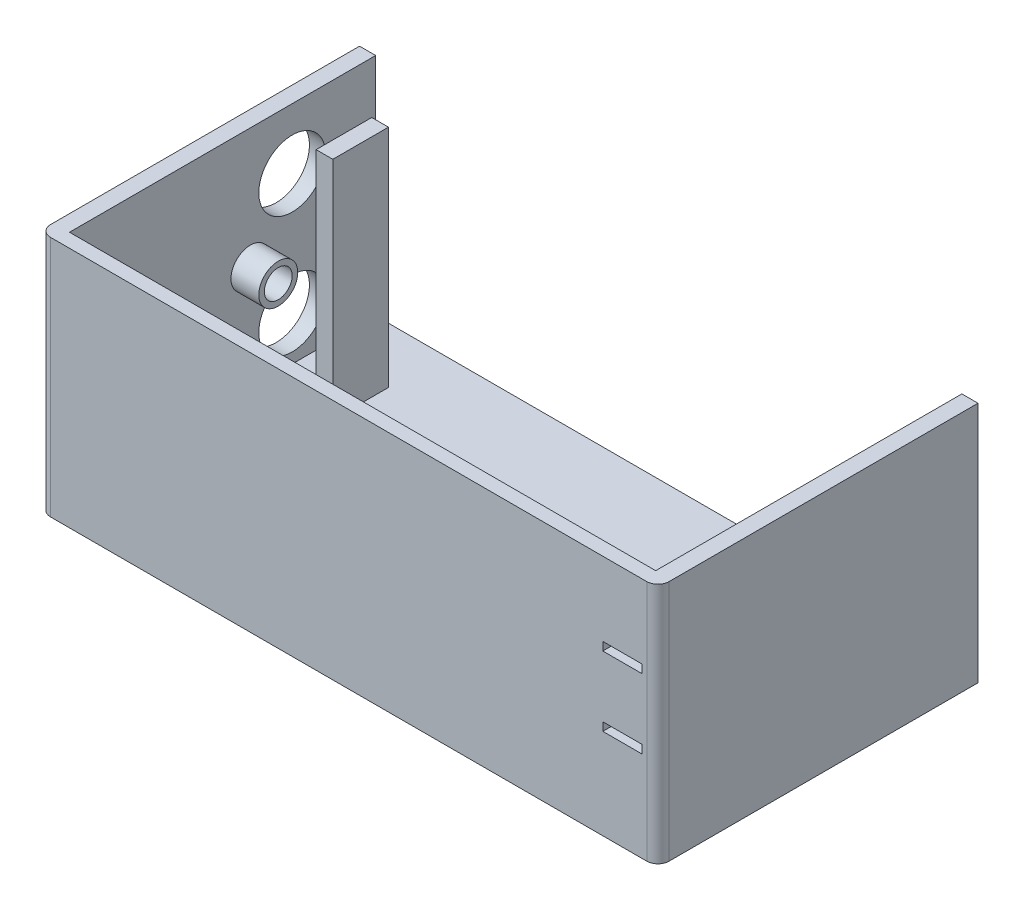
SolidWorks part; units mm, degrees
ref_plane "Front Plane" through (0, 0, 0) normal (0, 0, 1) x (1, 0, 0)
ref_plane "Top Plane" through (0, 0, 0) normal (0, 1, 0) x (1, 0, 0)
ref_plane "Right Plane" through (0, 0, 0) normal (1, 0, 0) x (0, 0, -1)
sketch "Sketch1" plane through (0, 0, 0) normal (0, 1, 0) x (1, 0, 0)
  line L1 (55.55, -30) -> (-55.55, -30)
  line L2 (55.55, -30) -> (55.55, 30)
  line L3 (55.55, 30) -> (-55.55, 30)
  line L4 (-55.55, -30) -> (-55.55, 30)
  line L5 (55.55, -30) -> (-55.55, 30) construction
  line L6 (55.55, 30) -> (-55.55, -30) construction
  point P0 (0, 0)
  dimension "D1" = 111.1
  dimension "D2" = 60
extrude "Boss-Extrude1" add sketch "Sketch1" along normal blind 3
sketch "Sketch2" plane through (0, 3, 0) normal (0, 1, 0) x (1, 0, 0)
  line L1 (52.65, -27.5) -> (-52.65, -27.5)
  line L2 (52.65, -27.5) -> (52.65, 27.5)
  line L3 (52.65, 27.5) -> (-52.65, 27.5)
  line L4 (-52.65, -27.5) -> (-52.65, 27.5)
  line L5 (52.65, -27.5) -> (-52.65, 27.5) construction
  line L6 (52.65, 27.5) -> (-52.65, -27.5) construction
  line L7 (55.55, 30) -> (-55.55, 30)
  line L8 (55.55, 30) -> (55.55, -30)
  line L9 (55.55, -30) -> (-55.55, -30)
  line L10 (-55.55, 30) -> (-55.55, -30)
  line L11 (55.55, 30) -> (-55.55, -30) construction
  line L12 (55.55, -30) -> (-55.55, 30) construction
  point P0 (0, 0)
  point P6 (0, 0)
  dimension "D1" = 105.3
  dimension "D2" = 55
extrude "Boss-Extrude2" add sketch "Sketch2" along normal blind 40.5
sketch "Sketch5" plane through (0, 0, -30) normal (0, 0, -1) x (-1, 0, 0)
  line L0 (0, 43.5) -> (0, 0) construction
  line L1 (-55.55, 43.5) -> (55.55, 43.5) construction
  line L2 (-55.55, 43.5) -> (0, 43.5) construction
  line L3 (-27.775, 43.5) -> (-27.775, 0) construction
  line L4 (-55.55, 0) -> (55.55, 0) construction
  circle A0 centre (-27.775, 21.75) radius 21
  circle A1 centre (27.775, 21.75) radius 21
  dimension "D1" = 42
extrude "Boss-Extrude4" add sketch "Sketch5" along normal blind 15
sketch "Sketch6" plane through (0, 0, -45) normal (0, 0, -1) x (-1, 0, 0)
  line L0 (-27.775, 42.75) -> (-27.775, 0.75) construction
  line L1 (27.775, 42.75) -> (27.775, 0.75) construction
  line L3 (-20.025, 3.25) -> (-35.525, 3.25)
  line L4 (-20.025, 3.25) -> (-20.025, 40.25)
  line L5 (-20.025, 40.25) -> (-35.525, 40.25)
  line L6 (-35.525, 3.25) -> (-35.525, 40.25)
  line L7 (-20.025, 3.25) -> (-35.525, 40.25) construction
  line L8 (-20.025, 40.25) -> (-35.525, 3.25) construction
  line L9 (35.525, 3.25) -> (20.025, 3.25)
  line L10 (35.525, 3.25) -> (35.525, 40.25)
  line L11 (35.525, 40.25) -> (20.025, 40.25)
  line L12 (20.025, 3.25) -> (20.025, 40.25)
  line L13 (35.525, 3.25) -> (20.025, 40.25) construction
  line L14 (35.525, 40.25) -> (20.025, 3.25) construction
  circle A0 centre (-27.775, 21.75) radius 21 construction
  circle A1 centre (-27.775, 21.75) radius 21 construction
  circle A2 centre (27.775, 21.75) radius 21 construction
  circle A3 centre (27.775, 21.75) radius 21 construction
  point P14 (-27.775, 21.75)
  point P19 (27.775, 21.75)
  dimension "D1" = 15.5
  dimension "D2" = 37
extrude "Cut-Extrude1" cut sketch "Sketch6" against normal blind 21
sketch "Sketch8" plane through (0, 0, -45) normal (0, 0, -1) x (-1, 0, 0)
  line L0 (-27.775, 42.75) -> (-27.775, 0.75) construction
  line L2 (-21.625, 4.6) -> (-33.925, 4.6)
  line L3 (-21.625, 4.6) -> (-21.625, 38.9)
  line L4 (-21.625, 38.9) -> (-33.925, 38.9)
  line L5 (-33.925, 4.6) -> (-33.925, 38.9)
  line L6 (-21.625, 4.6) -> (-33.925, 38.9) construction
  line L7 (-21.625, 38.9) -> (-33.925, 4.6) construction
  circle A0 centre (-27.775, 21.75) radius 21 construction
  circle A1 centre (-27.775, 21.75) radius 21 construction
  circle A2 centre (-27.775, 21.75) radius 21
  dimension "D1" = 12.3
  dimension "D2" = 34.3
extrude "Boss-Extrude5" add sketch "Sketch8" against normal blind 1
sketch "Sketch9" plane through (0, 0, -45) normal (0, 0, -1) x (-1, 0, 0)
  line L0 (27.775, 42.75) -> (27.775, 0.75) construction
  line L2 (33.925, 4.6) -> (21.625, 4.6)
  line L3 (33.925, 4.6) -> (33.925, 38.9)
  line L4 (33.925, 38.9) -> (21.625, 38.9)
  line L5 (21.625, 4.6) -> (21.625, 38.9)
  line L6 (33.925, 4.6) -> (21.625, 38.9) construction
  line L7 (33.925, 38.9) -> (21.625, 4.6) construction
  circle A0 centre (27.775, 21.75) radius 21 construction
  circle A1 centre (27.775, 21.75) radius 21 construction
  circle A2 centre (27.775, 21.75) radius 21
  point P7 (27.775, 21.75)
  dimension "D1" = 12.3
  dimension "D2" = 34.3
extrude "Boss-Extrude6" add sketch "Sketch9" against normal blind 1
sketch "Sketch10" plane through (0, 0, -27.5) normal (0, 0, 1) x (1, 0, 0)
  line L0 (0, 43.5) -> (0, 0) construction
  line L1 (-55.55, 43.5) -> (55.55, 43.5) construction
  line L3 (63.1223, -12.5986) -> (-63.1223, -12.5986)
  line L4 (63.1223, -12.5986) -> (63.1223, 56.0986)
  line L5 (63.1223, 56.0986) -> (-63.1223, 56.0986)
  line L6 (-63.1223, -12.5986) -> (-63.1223, 56.0986)
  line L7 (63.1223, -12.5986) -> (-63.1223, 56.0986) construction
  line L8 (63.1223, 56.0986) -> (-63.1223, -12.5986) construction
  point P5 (0, 21.75)
extrude "Cut-Extrude3" cut sketch "Sketch10" against normal blind 53
sketch "Sketch12" plane through (0, 0, -27.5) normal (0, 0, -1) x (-1, 0, 0)
  line L0 (52.65, 8.7) -> (51.65, 8.7)
  line L1 (52.65, 43.5) -> (52.65, 3) construction
  line L2 (51.65, 8.7) -> (51.65, 7.2)
  line L3 (51.65, 7.2) -> (52.65, 7.2)
  line L4 (0, 43.5) -> (0, 0) construction
  line L5 (52.65, 43.5) -> (-52.65, 43.5) construction
  line L6 (0, 21.75) -> (55.55, 21.75) construction
  line L7 (55.55, 43.5) -> (55.55, 0) construction
  line L8 (52.65, 25.35) -> (51.65, 25.35)
  line L9 (51.65, 25.35) -> (51.65, 23.85)
  line L10 (51.65, 23.85) -> (52.65, 23.85)
  line L11 (52.65, 23.85) -> (52.65, 25.35)
  line L12 (52.65, 19.65) -> (52.65, 18.15)
  line L13 (51.65, 19.65) -> (52.65, 19.65)
  line L14 (51.65, 18.15) -> (51.65, 19.65)
  line L15 (52.65, 18.15) -> (51.65, 18.15)
  line L16 (52.65, 3) -> (-52.65, 3) construction
  line L18 (-51.65, 7.2) -> (-52.65, 7.2)
  line L19 (-51.65, 8.7) -> (-51.65, 7.2)
  line L20 (-52.65, 8.7) -> (-51.65, 8.7)
  line L21 (-52.65, 19.65) -> (-52.65, 18.15)
  line L22 (-52.65, 18.15) -> (-51.65, 18.15)
  line L23 (-51.65, 18.15) -> (-51.65, 19.65)
  line L24 (-51.65, 19.65) -> (-52.65, 19.65)
  line L25 (-52.65, 23.85) -> (-52.65, 25.35)
  line L26 (-51.65, 23.85) -> (-52.65, 23.85)
  line L27 (-51.65, 25.35) -> (-51.65, 23.85)
  line L28 (-52.65, 25.35) -> (-51.65, 25.35)
  line L29 (-52.65, 25.35) -> (-52.65, 23.85)
  line L30 (-52.65, 19.65) -> (-52.65, 18.15)
  line L31 (-52.65, 8.7) -> (-52.65, 7.2)
  line M15 (52.65, 43.5) -> (52.65, 3)
  line M17 (-52.65, 3) -> (-52.65, 43.5)
  dimension "D1" = 1
  dimension "D2" = 1.5
  dimension "D3" = 2.1
  dimension "D4" = 4.2
extrude "Boss-Extrude8" add sketch "Sketch12" against normal blind 2 contours L15 L13 L14 M15 | L2 L3 L0 M15 | L23 L24 L22 M17 | L28 L26 L27 M17 | L9 L10 L11 L8 | L19 L18 L31 L20
fillet "Fillet1" radius 2 2 edges at (-55.55, 21.75, 30) (55.55, 21.75, 30)
sketch "Sketch13" plane through (-52.65, 0, 0) normal (1, 0, 0) x (0, 0, -1)
  line L0 (-28, 0) -> (-28, 43.5) construction
  line L2 (-25, 25.75) -> (-27, 25.75)
  line L3 (-24, 24.75) -> (-24, 18.75)
  line L4 (-25, 17.75) -> (-27, 17.75)
  line L5 (-28, 24.75) -> (-28, 18.75)
  line L6 (-24, 25.75) -> (-28, 17.75) construction
  line L7 (-24, 17.75) -> (-28, 25.75) construction
  line L8 (12.5, 32.625) -> (12.5, 10.875) construction
  line L11 (27.5, 43.5) -> (27.5, 0) construction
  arc A1 (-24, 18.75) -> (-25, 17.75) centre (-25, 18.75) cw
  arc A2 (-27, 17.75) -> (-28, 18.75) centre (-27, 18.75) cw
  arc A3 (-27, 25.75) -> (-28, 24.75) centre (-27, 24.75) ccw
  arc A4 (-25, 25.75) -> (-24, 24.75) centre (-25, 24.75) cw
  circle A5 centre (12.5, 32.625) radius 6
  circle A6 centre (12.5, 10.875) radius 6
  circle A7 centre (5, 21.75) radius 2.5
  point P0 (-26, 21.75)
  point P21 (-28, 21.75)
  point P25 (12.5, 21.75)
  dimension "D1" = 4
  dimension "D3" = 1
  dimension "D4" = 12
  dimension "D6" = 5
  dimension "D2" = 8
  dimension "D5" = 15
  dimension "D7" = 7.5
extrude "Cut-Extrude4" cut sketch "Sketch13" against normal blind 14
sketch "Sketch15" plane through (0, 3, 0) normal (0, 1, 0) x (1, 0, 0)
  line L1 (-43.35, 17.5) -> (-40.35, 17.5)
  line L2 (-43.35, 17.5) -> (-43.35, 7.5)
  line L3 (-43.35, 7.5) -> (-40.35, 7.5)
  line L4 (-40.35, 17.5) -> (-40.35, 7.5)
  line L5 (-43.35, 17.5) -> (-40.35, 7.5) construction
  line L6 (-43.35, 7.5) -> (-40.35, 17.5) construction
  line L8 (-52.65, 27.5) -> (-52.65, -27.5) construction
  line L9 (52.65, 27.5) -> (-52.65, 27.5) construction
  point P0 (-41.85, 12.5)
  point P5 (0, 0)
  point P11 (0, 0)
  dimension "D1" = 3
  dimension "D2" = 10
  dimension "D3" = 12.3
  dimension "D4" = 15
extrude "Boss-Extrude9" add sketch "Sketch15" along normal blind 40.5
sketch "Sketch16" plane through (-55.55, 0, 0) normal (-1, 0, 0) x (0, 0, 1)
  circle A0 centre (-5, 21.75) radius 3.5
  dimension "D1" = 7
extrude "Cut-Extrude5" cut sketch "Sketch16" against normal blind 1
sketch "Sketch17" plane through (0, 0, 27.5) normal (0, 0, -1) x (-1, 0, 0)
  line L0 (-52.65, 43.5) -> (-52.65, 3) construction
  line L1 (-52.65, 17.75) -> (-45.65, 17.75)
  line L2 (-52.65, 17.75) -> (-52.65, 28.75)
  line L3 (-52.65, 28.75) -> (-45.65, 28.75)
  line L4 (-45.65, 17.75) -> (-45.65, 28.75)
  line L5 (-52.65, 17.75) -> (-45.65, 28.75) construction
  line L6 (-52.65, 28.75) -> (-45.65, 17.75) construction
  point P0 (-49.15, 23.25)
  point P7 (0, 0)
  point P8 (-52.65, 23.25)
  dimension "D1" = 11
  dimension "D2" = 7
extrude "Boss-Extrude10" add sketch "Sketch17" along normal blind 14
sketch "Sketch18" plane through (0, 0, 27.5) normal (0, 0, -1) x (-1, 0, 0)
  line L1 (-45.65, 28.75) -> (-52.65, 28.75)
  line L2 (-45.65, 28.75) -> (-45.65, 30.25)
  line L3 (-45.65, 30.25) -> (-52.65, 30.25)
  line L4 (-52.65, 28.75) -> (-52.65, 30.25)
  line L5 (-45.65, 17.75) -> (-52.65, 17.75)
  line L6 (-45.65, 17.75) -> (-45.65, 16.25)
  line L7 (-45.65, 16.25) -> (-52.65, 16.25)
  line L8 (-52.65, 17.75) -> (-52.65, 16.25)
  dimension "D1" = 7
  dimension "D2" = 1.5
  dimension "D3" = 1.5
  dimension "D4" = 7
extrude "Cut-Extrude6" cut sketch "Sketch18" against normal blind 14
sketch "Sketch19" plane through (-52.65, 0, 0) normal (1, 0, 0) x (0, 0, -1)
  circle A0 centre (5, 21.75) radius 3.5
  circle A1 centre (5, 21.75) radius 2.5 construction
  circle A2 centre (5, 21.75) radius 2.5
  dimension "D1" = 7
extrude "Boss-Extrude11" add sketch "Sketch19" along normal blind 5
